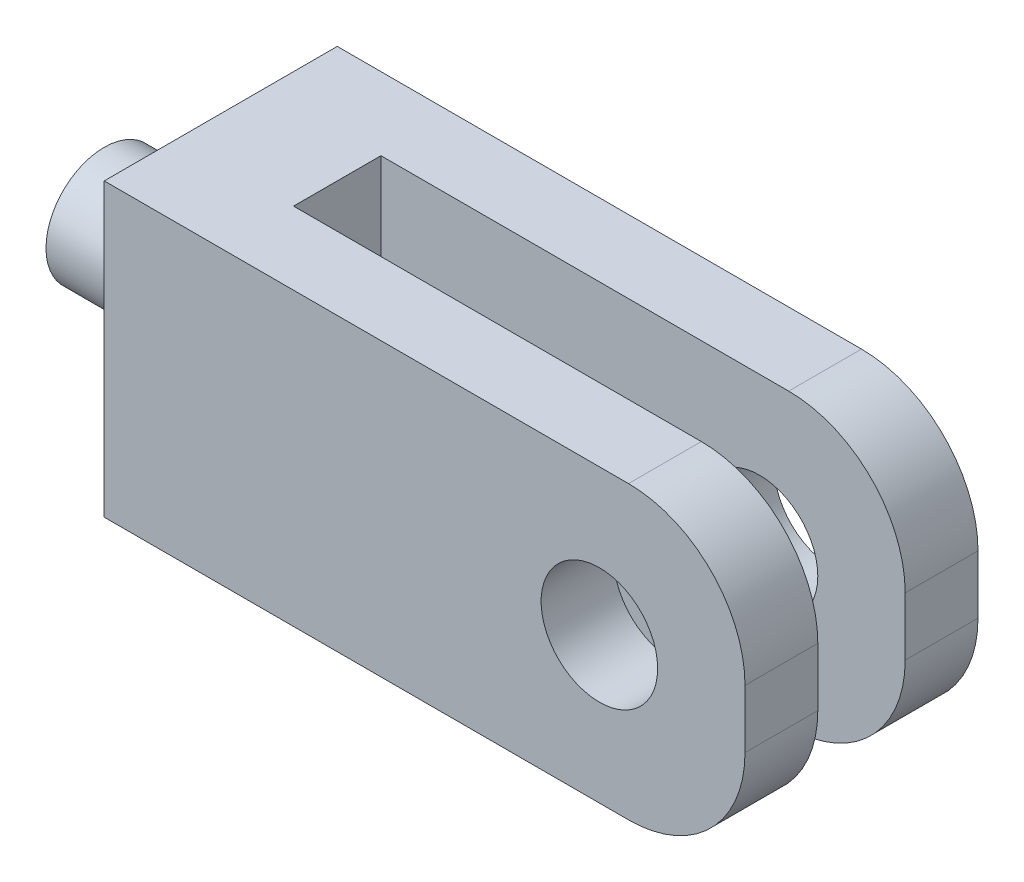
SolidWorks part; units mm, degrees
ref_plane "Front Plane" through (0, 0, 0) normal (0, 0, 1) x (1, 0, 0)
ref_plane "Top Plane" through (0, 0, 0) normal (0, 1, 0) x (1, 0, 0)
ref_plane "Right Plane" through (0, 0, 0) normal (1, 0, 0) x (0, 0, -1)
sketch "Sketch1" plane through (0, 0, 0) normal (0, 0, 1) x (1, 0, 0)
  line L1 (82.5, 37.5) -> (-82.5, 37.5)
  line L2 (82.5, 37.5) -> (82.5, -37.5)
  line L3 (82.5, -37.5) -> (-82.5, -37.5)
  line L4 (-82.5, 37.5) -> (-82.5, -37.5)
  line L5 (82.5, 37.5) -> (-82.5, -37.5) construction
  line L6 (82.5, -37.5) -> (-82.5, 37.5) construction
  point P0 (0, 0)
  dimension "D1" = 165
  dimension "D2" = 75
extrude "Boss-Extrude1" add sketch "Sketch1" along normal blind 60 contours L1 L4 L3 L2
sketch "Sketch2" plane through (82.5, 0, 0) normal (1, 0, 0) x (0, 0, -1)
  line L0 (-60, -37.5) -> (0, -37.5) construction
  line L1 (-41.25, -37.5) -> (-18.75, -37.5)
  line L2 (-41.25, -37.5) -> (-41.25, 37.5)
  line L3 (-41.25, 37.5) -> (-18.75, 37.5)
  line L4 (-18.75, -37.5) -> (-18.75, 37.5)
  line L5 (-60, 37.5) -> (0, 37.5) construction
  point P8 (-30, -37.5)
  dimension "D1" = 22.5
  dimension "D2" = 30
extrude "Cut-Extrude1" cut sketch "Sketch2" against normal blind 135
fillet "Fillet1" radius 30 4 edges at (82.5, -37.5, 50.625) (82.5, -37.5, 9.375) (82.5, 37.5, 9.375) (82.5, 37.5, 50.625)
sketch "Sketch3" plane through (0, 0, 60) normal (0, 0, 1) x (1, 0, 0)
  circle A0 centre (45, 0) radius 15
  dimension "D1" = 30
  dimension "D2" = 45
extrude "Cut-Extrude2" cut sketch "Sketch3" against normal through all
sketch "Sketch4" plane through (-82.5, 0, 0) normal (-1, 0, 0) x (0, 0, 1)
  line L0 (0, 37.5) -> (60, -37.5) construction
  circle A0 centre (30, 0) radius 15
  dimension "D1" = 30
extrude "Boss-Extrude2" add sketch "Sketch4" along normal blind 30
